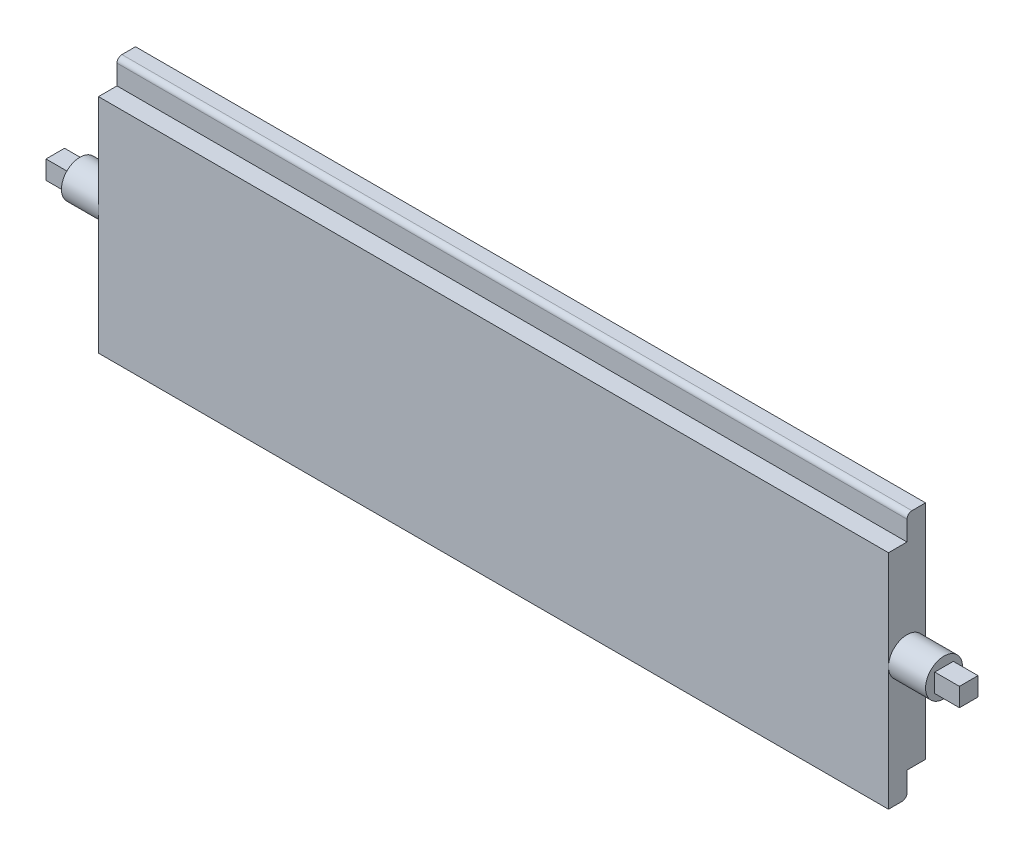
SolidWorks part; units mm, degrees
ref_plane "Front Plane" through (0, 0, 0) normal (0, 0, 1) x (1, 0, 0)
ref_plane "Top Plane" through (0, 0, 0) normal (0, 1, 0) x (1, 0, 0)
ref_plane "Right Plane" through (0, 0, 0) normal (1, 0, 0) x (0, 0, -1)
sketch "Sketch1" plane through (0, 0, 0) normal (0, 0, 1) x (1, 0, 0)
  line L1 (-101.6, -31.75) -> (101.6, -31.75)
  line L2 (-101.6, -31.75) -> (-101.6, 31.75)
  line L3 (-101.6, 31.75) -> (101.6, 31.75)
  line L4 (101.6, -31.75) -> (101.6, 31.75)
  line L5 (-101.6, -31.75) -> (101.6, 31.75) construction
  line L6 (-101.6, 31.75) -> (101.6, -31.75) construction
  point P0 (0, 0)
  dimension "D1" = 63.5
  dimension "D2" = 203.2
extrude "Boss-Extrude1" add sketch "Sketch1" along normal mid plane 9.525
sketch "Sketch2" plane through (101.6, 0, 0) normal (1, 0, 0) x (0, 0, -1)
  line L0 (0, 50.8) -> (0, 23.0111) construction
  line L2 (-4.7625, 0) -> (8.5114, 0) construction
  circle A0 centre (0, 0) radius 4.7625
  dimension "D1" = 9.525
extrude "Boss-Extrude2" add sketch "Sketch2" along normal blind 9.525
sketch "Sketch3" plane through (111.125, 0, 0) normal (1, 0, 0) x (0, 0, -1)
  line L5 (-2.3876, -2.3876) -> (2.3876, -2.3876)
  line L6 (-2.3876, -2.3876) -> (-2.3876, 2.3876)
  line L7 (-2.3876, 2.3876) -> (2.3876, 2.3876)
  line L8 (2.3876, -2.3876) -> (2.3876, 2.3876)
  line L9 (-2.3876, -2.3876) -> (2.3876, 2.3876) construction
  line L10 (-2.3876, 2.3876) -> (2.3876, -2.3876) construction
  point P0 (0, 0)
  dimension "D1" = 4.7752
  dimension "D2" = 4.7752
extrude "Boss-Extrude3" add sketch "Sketch3" along normal blind 6.35
mirror "Mirror1" about plane through (0, 0, 0) normal (1, 0, 0) of "Boss-Extrude3", "Boss-Extrude2"
sketch "Sketch4" plane through (0, 0, 4.7625) normal (0, 0, 1) x (1, 0, 0)
  line L0 (101.6, 0) -> (101.6, 31.75) construction
  line L1 (-101.6, 31.75) -> (101.6, 31.75)
  line L2 (-101.6, 31.75) -> (-101.6, 25.4)
  line L3 (-101.6, 25.4) -> (101.6, 25.4)
  line L4 (101.6, 31.75) -> (101.6, 25.4)
  dimension "D1" = 6.35
extrude "Cut-Extrude1" cut sketch "Sketch4" against normal blind 4.7625
sketch "Sketch5" plane through (0, 0, -4.7625) normal (0, 0, -1) x (-1, 0, 0)
  line L0 (101.6, 0) -> (101.6, -31.75) construction
  line L1 (-101.6, -31.75) -> (101.6, -31.75)
  line L2 (-101.6, -31.75) -> (-101.6, -25.4)
  line L3 (-101.6, -25.4) -> (101.6, -25.4)
  line L4 (101.6, -31.75) -> (101.6, -25.4)
  dimension "D1" = 6.35
extrude "Cut-Extrude2" cut sketch "Sketch5" against normal blind 4.7625
fillet "Fillet1" radius 1.27 2 edges at (0, -31.75, 0) (0, 31.75, 0)
